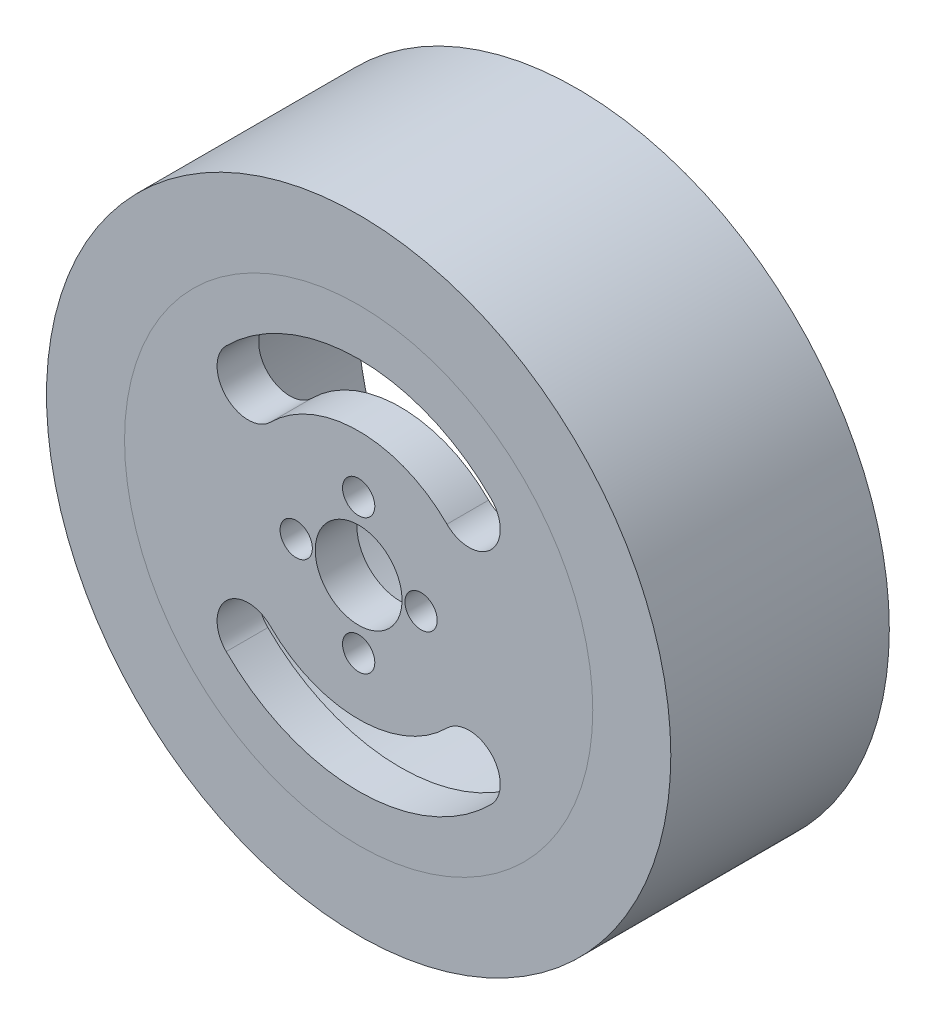
SolidWorks part; units mm, degrees
ref_plane "正面" through (0, 0, 0) normal (0, 0, 1) x (1, 0, 0)
ref_plane "平面" through (0, 0, 0) normal (0, 1, 0) x (1, 0, 0)
ref_plane "右側面" through (0, 0, 0) normal (1, 0, 0) x (0, 0, -1)
sketch "ｽｹｯﾁ1" plane through (0, 0, 0) normal (0, 0, 1) x (1, 0, 0)
  circle A0 centre (0, 0) radius 22.5
  dimension "D1" = 45
extrude "ﾎﾞｽ - 押し出し1" add sketch "ｽｹｯﾁ1" along normal blind 21
sketch "ｽｹｯﾁ2" plane through (0, 0, 0) normal (0, 0, -1) x (-1, 0, 0)
  circle A0 centre (0, 0) radius 21
  dimension "D1" = 42
extrude "ｶｯﾄ - 押し出し1" cut sketch "ｽｹｯﾁ2" against normal blind 17
sketch "ｽｹｯﾁ3" plane through (0, 0, 17) normal (0, 0, -1) x (-1, 0, 0)
  line L0 (0, 0) -> (-10.6066, 10.6066) construction
  line L1 (0, 0) -> (10.6066, 10.6066) construction
  line L2 (10.6066, 10.6066) -> (-10.6066, 10.6066) construction
  line L3 (0, 0) -> (-21, 0) construction
  circle A0 centre (0, 0) radius 4.17
  circle A1 centre (0, 0) radius 6.5 construction
  circle A2 centre (0, 0) radius 6 construction
  circle A3 centre (0, 6.5) radius 1.55
  circle A4 centre (0, -6.5) radius 1.55
  circle A5 centre (6, 0) radius 1.55
  circle A6 centre (-6, 0) radius 1.55
  circle A7 centre (-10.6066, 10.6066) radius 3
  circle A8 centre (10.6066, 10.6066) radius 3
  arc A9 (-12.7279, 12.7279) -> (12.7279, 12.7279) centre (0, 0) cw
  arc A10 (-8.4853, 8.4853) -> (8.4853, 8.4853) centre (0, 0) cw
  circle A11 centre (0, 0) radius 21 construction
  circle A12 centre (10.6066, -10.6066) radius 3
  circle A13 centre (-10.6066, -10.6066) radius 3
  arc A14 (-8.4853, -8.4853) -> (8.4853, -8.4853) centre (0, 0) ccw
  arc A15 (-12.7279, -12.7279) -> (12.7279, -12.7279) centre (0, 0) ccw
  dimension "D1" = 8.34
  dimension "D2" = 3.1
  dimension "D3" = 13
  dimension "D4" = 12
  dimension "D5" = 6
  dimension "D6" = 15
extrude "ｶｯﾄ - 押し出し2" cut sketch "ｽｹｯﾁ3" against normal through all contours A7 A10 A8 A9 | A7 | A8 | A0 | A5 | A3 | A6 | A4 | A13 | A13 A15 A12 A14 | A12
sketch "ｽｹｯﾁ5" plane through (0, 0, 21) normal (0, 0, 1) x (1, 0, 0)
  circle A0 centre (0, 0) radius 30
  circle A1 centre (0, 0) radius 22.5 construction
  circle A2 centre (0, 0) radius 22.5
  dimension "D1" = 60
extrude "ﾎﾞｽ - 押し出し2" add sketch "ｽｹｯﾁ5" against normal up to surface (21 mm away) separate body up to face at (-21, 0, 0)
